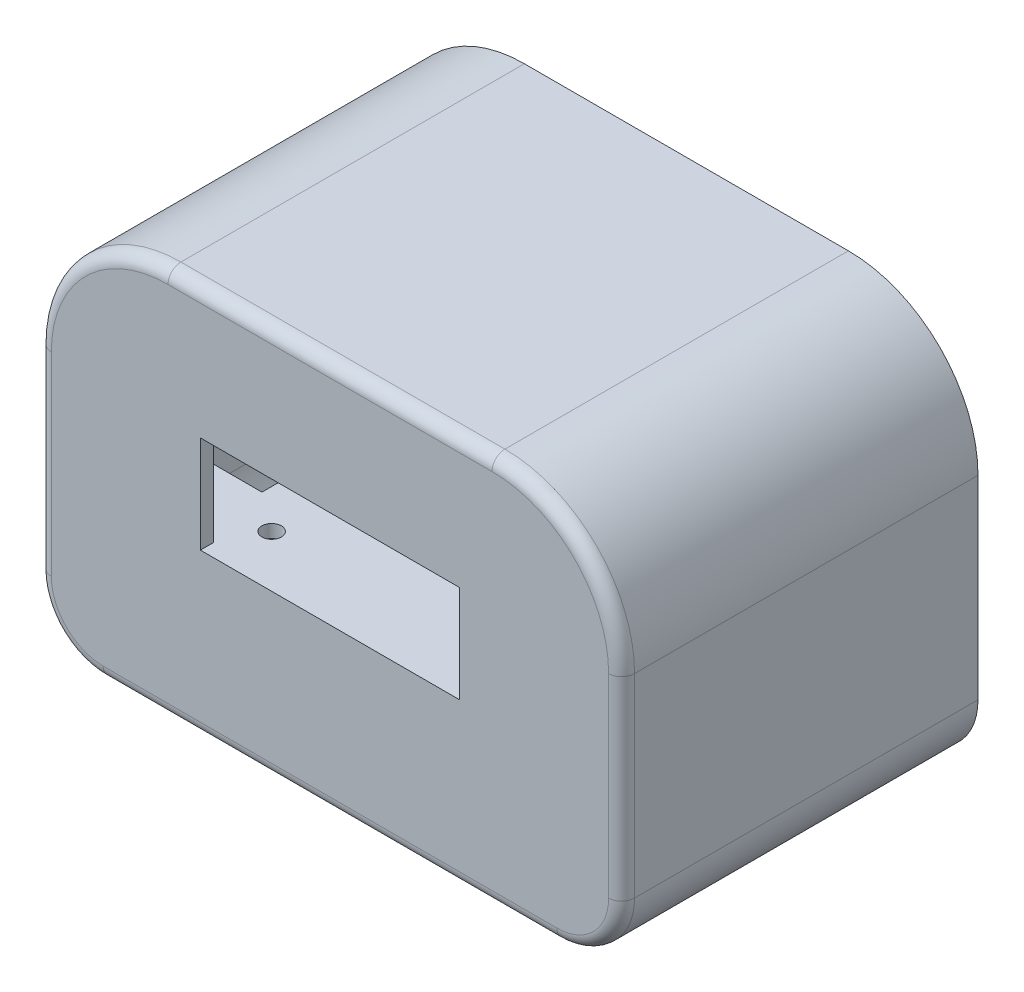
SolidWorks part; units mm, degrees
ref_plane "Front Plane" through (0, 0, 0) normal (0, 0, 1) x (1, 0, 0)
ref_plane "Top Plane" through (0, 0, 0) normal (0, 1, 0) x (1, 0, 0)
ref_plane "Right Plane" through (0, 0, 0) normal (1, 0, 0) x (0, 0, -1)
sketch "Sketch1" plane through (0, 0, 0) normal (0, 0, 1) x (1, 0, 0)
  line L1 (-25, 30) -> (25, 30)
  line L2 (-45, 10) -> (-45, -20)
  line L3 (-35, -30) -> (35, -30)
  line L4 (45, 10) -> (45, -20)
  line L5 (-45, 30) -> (45, -30) construction
  line L6 (-45, -30) -> (45, 30) construction
  arc A0 (35, -30) -> (45, -20) centre (35, -20) ccw
  arc A1 (-45, -20) -> (-35, -30) centre (-35, -20) ccw
  arc A2 (25, 30) -> (45, 10) centre (25, 10) cw
  arc A3 (-25, 30) -> (-45, 10) centre (-25, 10) ccw
  point P0 (0, 0)
  dimension "D1" = 20
  dimension "D4" = 10
  dimension "D2" = 90
  dimension "D3" = 60
extrude "Boss-Extrude1" add sketch "Sketch1" along normal blind 55
shell "Shell1" thickness 2
sketch "Sketch2" plane through (0, 0, 0) normal (0, 0, -1) x (-1, 0, 0)
  line L0 (-25, 30) -> (25, 30) construction
  line L1 (-23, 18.48) -> (-40.8773, 18.48)
  line L2 (-23, 18.48) -> (-23, 28)
  line L3 (0, 28) -> (0, -28) construction
  line L4 (-25, 28) -> (25, 28) construction
  line L5 (35, -28) -> (-35, -28) construction
  line L7 (23, 18.48) -> (40.8773, 18.48)
  line L8 (-23, 28) -> (-25, 28)
  line L9 (-45, -20) -> (-45, 10) construction
  line L10 (23, 18.48) -> (23, 28)
  line L11 (23, 28) -> (25, 28)
  arc A0 (-25, 28) -> (-43, 10) centre (-25, 10) ccw construction
  arc A1 (-40.8773, 18.48) -> (-25, 28) centre (-25, 10) cw
  arc A2 (40.8773, 18.48) -> (25, 28) centre (25, 10) ccw
  point P22 (-45, -5)
  dimension "D1" = 11.52
  dimension "D2" = 22
extrude "Boss-Extrude2" add sketch "Sketch2" against normal blind 10 contours L7 A2 L11 L10 | L1 A1 L8 L2
hole_wizard "M3x0.5 Tapped Hole1" positions "Sketch3" profile "Sketch4" tap size "M3x0.5" standard "ANSI Metric"
sketch "Sketch3" plane through (0, 0, 0) normal (0, 0, -1) x (-1, 0, 0)
  line L0 (-25, 30) -> (25, 30) construction
  line L1 (-45, -20) -> (-45, 10) construction
  line L2 (45, 10) -> (45, -20) construction
  point P0 (-28.5, 22)
  point P10 (28.5, 22)
  dimension "D1" = 8
  dimension "D2" = 16.5
  dimension "D3" = 16.5
sketch "Sketch4" plane through (28.5, 22, 0) normal (1, 0, 0) x (0, 1, 0)
  line L0 (0, 0) -> (0, 8.2511)
  line L1 (0, 8.2511) -> (1.25, 7.5)
  line L2 (1.25, 7.5) -> (1.25, 0)
  line L5 (1.25, 0) -> (0, 0)
  line L10 (0, 8.2511) -> (-1.25, 7.5) construction
  line L11 (0, -6.35) -> (0, 107.95) construction
  dimension "Tap Drill Dia." = 2.5
  dimension "Tap Drill Depth" = 7.5
  dimension "Drill Angle" = 118
sketch "Sketch5" plane through (0, 0, 0) normal (0, 0, -1) x (-1, 0, 0)
  line L0 (-43, -20) -> (-43, 10) construction
  line L1 (-43, -5) -> (43, -5)
  line L2 (-43, -5) -> (-43, -7)
  line L3 (-43, -7) -> (43, -7)
  line L4 (43, -5) -> (43, -7)
  line L5 (43, 10) -> (43, -20) construction
  line L7 (-25, 30) -> (25, 30) construction
  dimension "D1" = 35
  dimension "D2" = 2
extrude "Boss-Extrude3" add sketch "Sketch5" against normal up to next contours L1 L4 L3 L2
sketch "Sketch6" plane through (0, 0, 53) normal (0, 0, -1) x (-1, 0, 0)
  line L0 (-43, -5) -> (43, -5) construction
  line L1 (-20, -5) -> (20, -5)
  line L2 (-20, -5) -> (-20, 10)
  line L3 (-20, 10) -> (20, 10)
  line L4 (20, -5) -> (20, 10)
  point P6 (0, 10)
  dimension "D1" = 15
  dimension "D2" = 40
extrude "Cut-Extrude1" cut sketch "Sketch6" against normal blind 10
hole_wizard "Ø3.0mm Dowel Hole1" positions "Sketch7" profile "Sketch8" hole size "Ø3.0" standard "AS"
sketch "Sketch7" plane through (0, -5, 0) normal (0, 1, 0) x (1, 0, 0)
  line L0 (17, -34.5) -> (-17, -47) construction
  line L2 (-20, -55) -> (20, -55) construction
  line L3 (-17, -47) -> (-17, -22) construction
  point P0 (-17, -47)
  point P2 (-17, -22)
  point P4 (17, -34.5)
  point P11 (0, -40.75)
  point P14 (0, -55)
  point P20 (-17, -34.5)
  dimension "D1" = 25
  dimension "D2" = 34
  dimension "D3" = 8
sketch "Sketch8" plane through (-17, -5, 47) normal (1, 0, 0) x (0, 0, 1)
  line L0 (0, 0) -> (0, 4.9013)
  line L1 (0, 4.9013) -> (1.5, 4)
  line L2 (1.5, 4) -> (1.5, 0)
  line L5 (1.5, 0) -> (0, 0)
  line L10 (0, 4.9013) -> (-1.5, 4) construction
  line L11 (0, -6.35) -> (0, 107.95) construction
  dimension "Hole Dia." = 3
  dimension "Hole Depth" = 4
  dimension "Drill Angle" = 118
sketch "Sketch9" plane through (0, -5, 0) normal (0, 1, 0) x (1, 0, 0)
  line L0 (-43, -53) -> (-43, 0) construction
  line L1 (-43, -26.5) -> (-23, -26.5)
  line L2 (-43, -26.5) -> (-43, -42.5)
  line L3 (-43, -42.5) -> (-23, -42.5)
  line L4 (-23, -26.5) -> (-23, -42.5)
  line L5 (-17, -47) -> (-17, -22) construction
  point P6 (-17, -34.5)
  point P7 (-23, -34.5)
  dimension "D1" = 20
extrude "Cut-Extrude2" cut sketch "Sketch9" against normal up to surface (2 mm away) up to face at (-17, -7, 45.5)
fillet "Fillet1" radius 2 8 edges at (45, -5, 55) (42.0711, -27.0711, 55) (0, -30, 55) (-42.0711, -27.0711, 55) (-45, -5, 55) (-39.1421, 24.1421, 55) (0, 30, 55) (39.1421, 24.1421, 55)
